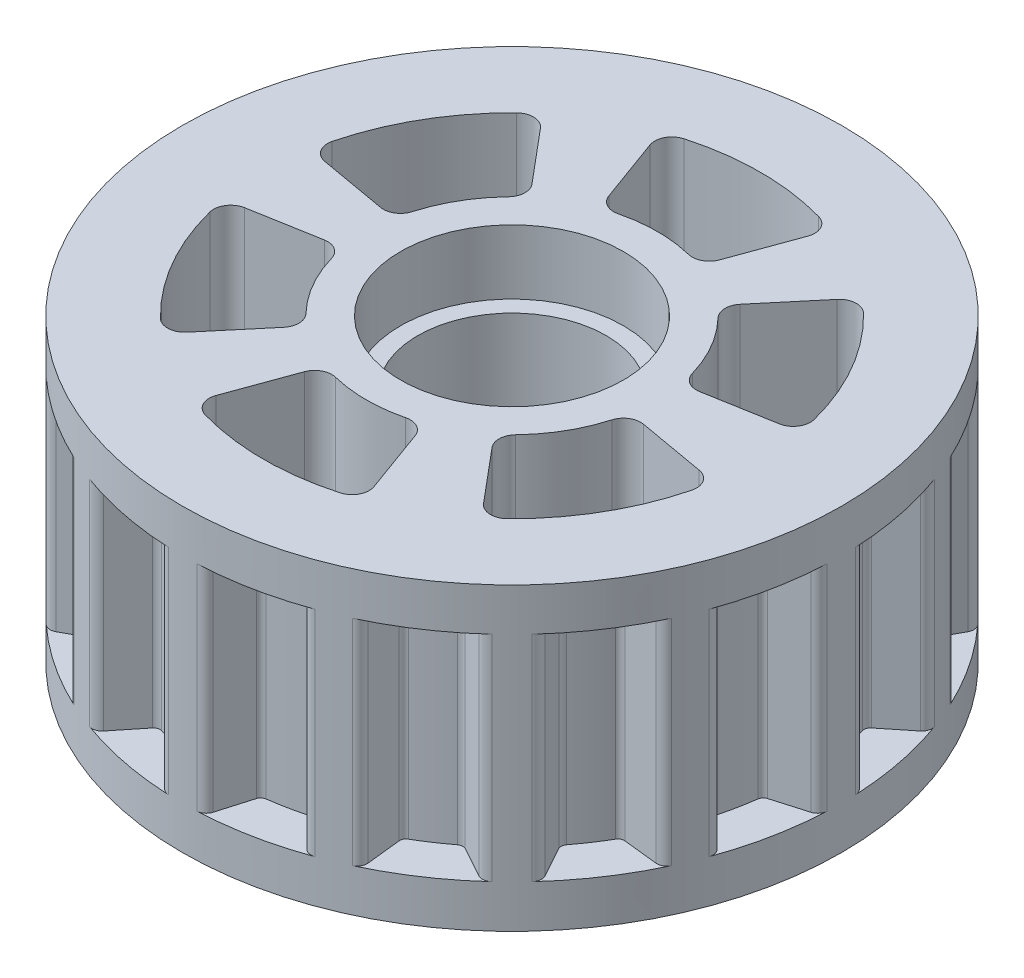
SolidWorks part; units mm, degrees
ref_plane "前视基准面" through (0, 0, 0) normal (0, 0, 1) x (1, 0, 0)
ref_plane "上视基准面" through (0, 0, 0) normal (0, 1, 0) x (1, 0, 0)
ref_plane "右视基准面" through (0, 0, 0) normal (1, 0, 0) x (0, 0, -1)
sketch "草图1" plane through (0, 0, 0) normal (0, 1, 0) x (1, 0, 0)
  line L0 (-135.6037, 0) -> (114.9676, 0) construction
  line L1 (0, 133.2517) -> (0, -98.6639) construction
  circle A0 centre (0, 0) radius 76.925
extrude "凸台-拉伸1" add sketch "草图1" along normal blind 10
ref_plane "基准面1" through (0, 10, 0) normal (0, 1, 0) x (1, 0, 0)
sketch "草图2" plane through (0, 10, 0) normal (0, 1, 0) x (1, 0, 0)
  line L0 (0, 47.7566) -> (0, -19.898) construction
  line L1 (-34.7968, 0) -> (37.1562, 0) construction
  line L2 (0, 0) -> (6.2332, 95.8691) construction
  line L3 (4.9909, 76.7629) -> (8.95, 63.2066) construction
  line L4 (0, 0) -> (18.3427, 92.2148) construction
  line L5 (5.4476, 75.1994) -> (7.729, 67.3874)
  line L6 (-5.4476, 75.1994) -> (-7.729, 67.3874)
  line L7 (23.7447, 71.5599) -> (18.6474, 65.2156)
  line L8 (33.8105, 67.3905) -> (32.9287, 59.3001)
  line L9 (49.322, 57.026) -> (42.1849, 53.1153)
  line L10 (57.026, 49.322) -> (53.1153, 42.1849)
  line L11 (67.3905, 33.8105) -> (59.3001, 32.9287)
  line L12 (71.5599, 23.7447) -> (65.2156, 18.6474)
  line L13 (75.1994, 5.4476) -> (67.3874, 7.729)
  line L14 (75.1994, -5.4476) -> (67.3874, -7.729)
  line L15 (71.5599, -23.7447) -> (65.2156, -18.6474)
  line L16 (67.3905, -33.8105) -> (59.3001, -32.9287)
  line L17 (57.026, -49.322) -> (53.1153, -42.1849)
  line L18 (49.322, -57.026) -> (42.1849, -53.1153)
  line L19 (33.8105, -67.3905) -> (32.9287, -59.3001)
  line L20 (23.7447, -71.5599) -> (18.6474, -65.2156)
  line L21 (5.4476, -75.1994) -> (7.729, -67.3874)
  line L22 (-5.4476, -75.1994) -> (-7.729, -67.3874)
  line L23 (-23.7447, -71.5599) -> (-18.6474, -65.2156)
  line L24 (-33.8105, -67.3905) -> (-32.9287, -59.3001)
  line L25 (-49.322, -57.026) -> (-42.1849, -53.1153)
  line L26 (-57.026, -49.322) -> (-53.1153, -42.1849)
  line L27 (-67.3905, -33.8105) -> (-59.3001, -32.9287)
  line L28 (-71.5599, -23.7447) -> (-65.2156, -18.6474)
  line L29 (-75.1994, -5.4476) -> (-67.3874, -7.729)
  line L30 (-75.1994, 5.4476) -> (-67.3874, 7.729)
  line L31 (-71.5599, 23.7447) -> (-65.2156, 18.6474)
  line L32 (-67.3905, 33.8105) -> (-59.3001, 32.9287)
  line L33 (-57.026, 49.322) -> (-53.1153, 42.1849)
  line L34 (-49.322, 57.026) -> (-42.1849, 53.1153)
  line L35 (-33.8105, 67.3905) -> (-32.9287, 59.3001)
  line L36 (-23.7447, 71.5599) -> (-18.6474, 65.2156)
  arc A0 (3.3396, 76.8525) -> (-3.3396, 76.8525) centre (0, 0) ccw
  arc A1 (17.0949, 64.7049) -> (18.6474, 65.2156) centre (17.4781, 66.1551) ccw
  arc A2 (23.7447, 71.5599) -> (26.3248, 72.2804) centre (25.5377, 70.1193) cw
  arc A3 (17.0949, 64.7049) -> (8.9678, 66.3214) centre (0, 0) ccw
  arc A4 (5.4476, 75.1994) -> (3.3396, 76.8525) centre (3.2398, 74.5546) ccw
  arc A5 (8.9678, 66.3214) -> (7.729, 67.3874) centre (9.1688, 67.8079) cw
  arc A6 (32.4956, 69.7244) -> (26.3248, 72.2804) centre (0, 0) ccw
  arc A7 (-8.9678, 66.3214) -> (-7.729, 67.3874) centre (-9.1688, 67.8079) ccw
  arc A8 (-5.4476, 75.1994) -> (-3.3396, 76.8525) centre (-3.2398, 74.5546) cw
  arc A9 (33.8105, 67.3905) -> (32.4956, 69.7244) centre (31.524, 67.6397) ccw
  arc A10 (33.6653, 57.8412) -> (32.9287, 59.3001) centre (34.4199, 59.1376) cw
  arc A11 (40.5551, 53.2376) -> (33.6653, 57.8412) centre (0, 0) ccw
  arc A12 (40.5551, 53.2376) -> (42.1849, 53.1153) centre (41.4641, 54.4308) ccw
  arc A13 (49.322, 57.026) -> (51.9814, 56.7044) centre (50.4272, 55.009) cw
  arc A14 (56.7044, 51.9814) -> (51.9814, 56.7044) centre (0, 0) ccw
  arc A15 (57.026, 49.322) -> (56.7044, 51.9814) centre (55.009, 50.4272) ccw
  arc A16 (53.2376, 40.5551) -> (53.1153, 42.1849) centre (54.4308, 41.4641) cw
  arc A17 (57.8412, 33.6653) -> (53.2376, 40.5551) centre (0, 0) ccw
  arc A18 (57.8412, 33.6653) -> (59.3001, 32.9287) centre (59.1376, 34.4199) ccw
  arc A19 (67.3905, 33.8105) -> (69.7244, 32.4956) centre (67.6397, 31.524) cw
  arc A20 (72.2804, 26.3248) -> (69.7244, 32.4956) centre (0, 0) ccw
  arc A21 (71.5599, 23.7447) -> (72.2804, 26.3248) centre (70.1193, 25.5377) ccw
  arc A22 (64.7049, 17.0949) -> (65.2156, 18.6474) centre (66.1551, 17.4781) cw
  arc A23 (66.3214, 8.9678) -> (64.7049, 17.0949) centre (0, 0) ccw
  arc A24 (66.3214, 8.9678) -> (67.3874, 7.729) centre (67.8079, 9.1688) ccw
  arc A25 (75.1994, 5.4476) -> (76.8525, 3.3396) centre (74.5546, 3.2398) cw
  arc A26 (76.8525, -3.3396) -> (76.8525, 3.3396) centre (0, 0) ccw
  arc A27 (75.1994, -5.4476) -> (76.8525, -3.3396) centre (74.5546, -3.2398) ccw
  arc A28 (66.3214, -8.9678) -> (67.3874, -7.729) centre (67.8079, -9.1688) cw
  arc A29 (64.7049, -17.0949) -> (66.3214, -8.9678) centre (0, 0) ccw
  arc A30 (64.7049, -17.0949) -> (65.2156, -18.6474) centre (66.1551, -17.4781) ccw
  arc A31 (71.5599, -23.7447) -> (72.2804, -26.3248) centre (70.1193, -25.5377) cw
  arc A32 (69.7244, -32.4956) -> (72.2804, -26.3248) centre (0, 0) ccw
  arc A33 (67.3905, -33.8105) -> (69.7244, -32.4956) centre (67.6397, -31.524) ccw
  arc A34 (57.8412, -33.6653) -> (59.3001, -32.9287) centre (59.1376, -34.4199) cw
  arc A35 (53.2376, -40.5551) -> (57.8412, -33.6653) centre (0, 0) ccw
  arc A36 (53.2376, -40.5551) -> (53.1153, -42.1849) centre (54.4308, -41.4641) ccw
  arc A37 (57.026, -49.322) -> (56.7044, -51.9814) centre (55.009, -50.4272) cw
  arc A38 (51.9814, -56.7044) -> (56.7044, -51.9814) centre (0, 0) ccw
  arc A39 (49.322, -57.026) -> (51.9814, -56.7044) centre (50.4272, -55.009) ccw
  arc A40 (40.5551, -53.2376) -> (42.1849, -53.1153) centre (41.4641, -54.4308) cw
  arc A41 (33.6653, -57.8412) -> (40.5551, -53.2376) centre (0, 0) ccw
  arc A42 (33.6653, -57.8412) -> (32.9287, -59.3001) centre (34.4199, -59.1376) ccw
  arc A43 (33.8105, -67.3905) -> (32.4956, -69.7244) centre (31.524, -67.6397) cw
  arc A44 (26.3248, -72.2804) -> (32.4956, -69.7244) centre (0, 0) ccw
  arc A45 (23.7447, -71.5599) -> (26.3248, -72.2804) centre (25.5377, -70.1193) ccw
  arc A46 (17.0949, -64.7049) -> (18.6474, -65.2156) centre (17.4781, -66.1551) cw
  arc A47 (8.9678, -66.3214) -> (17.0949, -64.7049) centre (0, 0) ccw
  arc A48 (8.9678, -66.3214) -> (7.729, -67.3874) centre (9.1688, -67.8079) ccw
  arc A49 (5.4476, -75.1994) -> (3.3396, -76.8525) centre (3.2398, -74.5546) cw
  arc A50 (-3.3396, -76.8525) -> (3.3396, -76.8525) centre (0, 0) ccw
  arc A51 (-5.4476, -75.1994) -> (-3.3396, -76.8525) centre (-3.2398, -74.5546) ccw
  arc A52 (-8.9678, -66.3214) -> (-7.729, -67.3874) centre (-9.1688, -67.8079) cw
  arc A53 (-17.0949, -64.7049) -> (-8.9678, -66.3214) centre (0, 0) ccw
  arc A54 (-17.0949, -64.7049) -> (-18.6474, -65.2156) centre (-17.4781, -66.1551) ccw
  arc A55 (-23.7447, -71.5599) -> (-26.3248, -72.2804) centre (-25.5377, -70.1193) cw
  arc A56 (-32.4956, -69.7244) -> (-26.3248, -72.2804) centre (0, 0) ccw
  arc A57 (-33.8105, -67.3905) -> (-32.4956, -69.7244) centre (-31.524, -67.6397) ccw
  arc A58 (-33.6653, -57.8412) -> (-32.9287, -59.3001) centre (-34.4199, -59.1376) cw
  arc A59 (-40.5551, -53.2376) -> (-33.6653, -57.8412) centre (0, 0) ccw
  arc A60 (-40.5551, -53.2376) -> (-42.1849, -53.1153) centre (-41.4641, -54.4308) ccw
  arc A61 (-49.322, -57.026) -> (-51.9814, -56.7044) centre (-50.4272, -55.009) cw
  arc A62 (-56.7044, -51.9814) -> (-51.9814, -56.7044) centre (0, 0) ccw
  arc A63 (-57.026, -49.322) -> (-56.7044, -51.9814) centre (-55.009, -50.4272) ccw
  arc A64 (-53.2376, -40.5551) -> (-53.1153, -42.1849) centre (-54.4308, -41.4641) cw
  arc A65 (-57.8412, -33.6653) -> (-53.2376, -40.5551) centre (0, 0) ccw
  arc A66 (-57.8412, -33.6653) -> (-59.3001, -32.9287) centre (-59.1376, -34.4199) ccw
  arc A67 (-67.3905, -33.8105) -> (-69.7244, -32.4956) centre (-67.6397, -31.524) cw
  arc A68 (-72.2804, -26.3248) -> (-69.7244, -32.4956) centre (0, 0) ccw
  arc A69 (-71.5599, -23.7447) -> (-72.2804, -26.3248) centre (-70.1193, -25.5377) ccw
  arc A70 (-64.7049, -17.0949) -> (-65.2156, -18.6474) centre (-66.1551, -17.4781) cw
  arc A71 (-66.3214, -8.9678) -> (-64.7049, -17.0949) centre (0, 0) ccw
  arc A72 (-66.3214, -8.9678) -> (-67.3874, -7.729) centre (-67.8079, -9.1688) ccw
  arc A73 (-75.1994, -5.4476) -> (-76.8525, -3.3396) centre (-74.5546, -3.2398) cw
  arc A74 (-76.8525, 3.3396) -> (-76.8525, -3.3396) centre (0, 0) ccw
  arc A75 (-75.1994, 5.4476) -> (-76.8525, 3.3396) centre (-74.5546, 3.2398) ccw
  arc A76 (-66.3214, 8.9678) -> (-67.3874, 7.729) centre (-67.8079, 9.1688) cw
  arc A77 (-64.7049, 17.0949) -> (-66.3214, 8.9678) centre (0, 0) ccw
  arc A78 (-64.7049, 17.0949) -> (-65.2156, 18.6474) centre (-66.1551, 17.4781) ccw
  arc A79 (-71.5599, 23.7447) -> (-72.2804, 26.3248) centre (-70.1193, 25.5377) cw
  arc A80 (-69.7244, 32.4956) -> (-72.2804, 26.3248) centre (0, 0) ccw
  arc A81 (-67.3905, 33.8105) -> (-69.7244, 32.4956) centre (-67.6397, 31.524) ccw
  arc A82 (-57.8412, 33.6653) -> (-59.3001, 32.9287) centre (-59.1376, 34.4199) cw
  arc A83 (-53.2376, 40.5551) -> (-57.8412, 33.6653) centre (0, 0) ccw
  arc A84 (-53.2376, 40.5551) -> (-53.1153, 42.1849) centre (-54.4308, 41.4641) ccw
  arc A85 (-57.026, 49.322) -> (-56.7044, 51.9814) centre (-55.009, 50.4272) cw
  arc A86 (-51.9814, 56.7044) -> (-56.7044, 51.9814) centre (0, 0) ccw
  arc A87 (-49.322, 57.026) -> (-51.9814, 56.7044) centre (-50.4272, 55.009) ccw
  arc A88 (-40.5551, 53.2376) -> (-42.1849, 53.1153) centre (-41.4641, 54.4308) cw
  arc A89 (-33.6653, 57.8412) -> (-40.5551, 53.2376) centre (0, 0) ccw
  arc A90 (-33.6653, 57.8412) -> (-32.9287, 59.3001) centre (-34.4199, 59.1376) ccw
  arc A91 (-33.8105, 67.3905) -> (-32.4956, 69.7244) centre (-31.524, 67.6397) cw
  arc A92 (-26.3248, 72.2804) -> (-32.4956, 69.7244) centre (0, 0) ccw
  arc A93 (-23.7447, 71.5599) -> (-26.3248, 72.2804) centre (-25.5377, 70.1193) ccw
  arc A94 (-17.0949, 64.7049) -> (-18.6474, 65.2156) centre (-17.4781, 66.1551) cw
  arc A95 (-8.9678, 66.3214) -> (-17.0949, 64.7049) centre (0, 0) ccw
  point P6 (4.9909, 76.7629)
  point P12 (8.0043, 66.4446)
  point P18 (0, 76.925)
  point P27 (8.0043, 66.4446)
  point P224 (0, 0)
  dimension "D1" = 3.72
  dimension "D4" = 2.3
  dimension "D5" = 1.5
  dimension "D2" = 20
  dimension "D6" = 16
extrude "凸台-拉伸2" add sketch "草图2" along normal blind 50
ref_plane "基准面2" through (0, 60, 0) normal (0, 1, 0) x (1, 0, 0)
sketch "草图3" plane through (0, 60, 0) normal (0, 1, 0) x (1, 0, 0)
  circle A0 centre (0, 0) radius 76.925
extrude "凸台-拉伸3" add sketch "草图3" along normal blind 10
sketch "草图4" plane through (0, 0, 0) normal (0, 1, 0) x (1, 0, 0)
  line L0 (-33.5811, 0) -> (24.5401, 0) construction
  line L1 (0, 61.9959) -> (0, -43.4833) construction
  circle A0 centre (0, 0) radius 26
extrude "切除-拉伸1" cut sketch "草图4" along normal blind 15
ref_plane "基准面3" through (0, 15, 0) normal (0, -1, 0) x (-1, 0, 0)
sketch "草图5" plane through (0, 15, 0) normal (0, -1, 0) x (-1, 0, 0)
  circle A0 centre (0, 0) radius 22
extrude "切除-拉伸2" cut sketch "草图5" against normal blind 40
ref_plane "基准面4" through (0, 55, 0) normal (0, -1, 0) x (-1, 0, 0)
sketch "草图6" plane through (0, 55, 0) normal (0, -1, 0) x (-1, 0, 0)
  circle A0 centre (0, 0) radius 26
extrude "切除-拉伸3" cut sketch "草图6" against normal through all
sketch "草图7" plane through (0, 0, 0) normal (0, 1, 0) x (1, 0, 0)
  line L0 (-40.6848, 0) -> (37.6711, 0) construction
  line L1 (0, 44.5596) -> (0, -36.5948) construction
  line L2 (0, 0) -> (28.6312, 78.6636) construction
  line L3 (12.9246, 35.5099) -> (18.4183, 50.604)
  line L4 (-12.9246, 35.5099) -> (-18.4183, 50.604)
  line L5 (37.2148, 6.562) -> (53.0335, 9.3512)
  line L6 (24.2902, 28.948) -> (34.6152, 41.2528)
  line L7 (24.2902, -28.948) -> (34.6152, -41.2528)
  line L8 (37.2148, -6.562) -> (53.0335, -9.3512)
  line L9 (-12.9246, -35.5099) -> (-18.4183, -50.604)
  line L10 (12.9246, -35.5099) -> (18.4183, -50.604)
  line L11 (-37.2148, -6.562) -> (-53.0335, -9.3512)
  line L12 (-24.2902, -28.948) -> (-34.6152, -41.2528)
  line L13 (-24.2902, 28.948) -> (-34.6152, 41.2528)
  line L14 (-37.2148, 6.562) -> (-53.0335, 9.3512)
  arc A0 (18.4183, 50.604) -> (15.7455, 55.8219) centre (14.6596, 51.9721) ccw
  arc A1 (12.9246, 35.5099) -> (8.201, 32.9961) centre (9.1658, 36.878) cw
  arc A2 (8.201, 32.9961) -> (-8.201, 32.9961) centre (0, 0) ccw
  arc A3 (15.7455, 55.8219) -> (-15.7455, 55.8219) centre (0, 0) ccw
  arc A4 (-12.9246, 35.5099) -> (-8.201, 32.9961) centre (-9.1658, 36.878) ccw
  arc A5 (-18.4183, 50.604) -> (-15.7455, 55.8219) centre (-14.6596, 51.9721) cw
  arc A6 (53.0335, 9.3512) -> (56.2159, 14.275) centre (52.3389, 13.2905) ccw
  arc A7 (37.2148, 6.562) -> (32.676, 9.3958) centre (36.5202, 10.5012) cw
  arc A8 (32.676, 9.3958) -> (24.475, 23.6003) centre (0, 0) ccw
  arc A9 (56.2159, 14.275) -> (40.4704, 41.5469) centre (0, 0) ccw
  arc A10 (24.2902, 28.948) -> (24.475, 23.6003) centre (27.3544, 26.3768) ccw
  arc A11 (34.6152, 41.2528) -> (40.4704, 41.5469) centre (37.6793, 38.6816) cw
  arc A12 (34.6152, -41.2528) -> (40.4704, -41.5469) centre (37.6793, -38.6816) ccw
  arc A13 (24.2902, -28.948) -> (24.475, -23.6003) centre (27.3544, -26.3768) cw
  arc A14 (24.475, -23.6003) -> (32.676, -9.3958) centre (0, 0) ccw
  arc A15 (40.4704, -41.5469) -> (56.2159, -14.275) centre (0, 0) ccw
  arc A16 (37.2148, -6.562) -> (32.676, -9.3958) centre (36.5202, -10.5012) ccw
  arc A17 (53.0335, -9.3512) -> (56.2159, -14.275) centre (52.3389, -13.2905) cw
  arc A18 (-18.4183, -50.604) -> (-15.7455, -55.8219) centre (-14.6596, -51.9721) ccw
  arc A19 (-12.9246, -35.5099) -> (-8.201, -32.9961) centre (-9.1658, -36.878) cw
  arc A20 (-8.201, -32.9961) -> (8.201, -32.9961) centre (0, 0) ccw
  arc A21 (-15.7455, -55.8219) -> (15.7455, -55.8219) centre (0, 0) ccw
  arc A22 (12.9246, -35.5099) -> (8.201, -32.9961) centre (9.1658, -36.878) ccw
  arc A23 (18.4183, -50.604) -> (15.7455, -55.8219) centre (14.6596, -51.9721) cw
  arc A24 (-53.0335, -9.3512) -> (-56.2159, -14.275) centre (-52.3389, -13.2905) ccw
  arc A25 (-37.2148, -6.562) -> (-32.676, -9.3958) centre (-36.5202, -10.5012) cw
  arc A26 (-32.676, -9.3958) -> (-24.475, -23.6003) centre (0, 0) ccw
  arc A27 (-56.2159, -14.275) -> (-40.4704, -41.5469) centre (0, 0) ccw
  arc A28 (-24.2902, -28.948) -> (-24.475, -23.6003) centre (-27.3544, -26.3768) ccw
  arc A29 (-34.6152, -41.2528) -> (-40.4704, -41.5469) centre (-37.6793, -38.6816) cw
  arc A30 (-34.6152, 41.2528) -> (-40.4704, 41.5469) centre (-37.6793, 38.6816) ccw
  arc A31 (-24.2902, 28.948) -> (-24.475, 23.6003) centre (-27.3544, 26.3768) cw
  arc A32 (-24.475, 23.6003) -> (-32.676, 9.3958) centre (0, 0) ccw
  arc A33 (-40.4704, 41.5469) -> (-56.2159, 14.275) centre (0, 0) ccw
  arc A34 (-37.2148, 6.562) -> (-32.676, 9.3958) centre (-36.5202, 10.5012) ccw
  arc A35 (-53.0335, 9.3512) -> (-56.2159, 14.275) centre (-52.3389, 13.2905) cw
  point P8 (-180.4102, 12.4871)
  point P9 (11.6287, 31.9495)
  point P10 (19.8372, 54.5022)
  point P15 (19.8372, 54.5022)
  point P18 (11.6287, 31.9495)
  point P27 (33.4835, 5.904)
  point P28 (57.1188, 10.0716)
  point P41 (21.8548, -26.0455)
  point P42 (37.2817, -44.4306)
  point P55 (-11.6287, -31.9495)
  point P56 (-19.8372, -54.5022)
  point P69 (-33.4835, -5.904)
  point P70 (-57.1188, -10.0716)
  point P83 (-21.8548, 26.0455)
  point P84 (-37.2817, 44.4306)
  point P96 (0, 0)
  dimension "D2" = 4
  dimension "D3" = 4
  dimension "D1" = 20
  dimension "D4" = 6
extrude "切除-拉伸4" cut sketch "草图7" along normal through all
